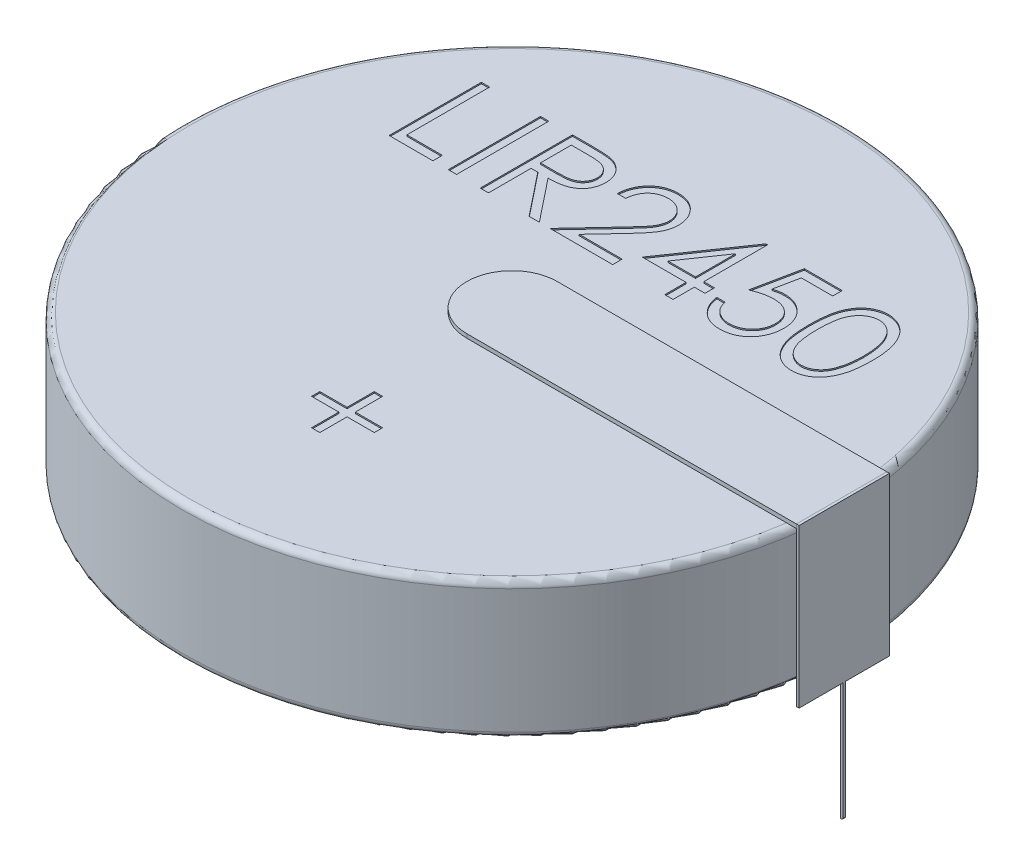
SolidWorks part; units mm, degrees
ref_plane "Plan de face" through (0, 0, 0) normal (0, 0, 1) x (1, 0, 0)
ref_plane "Plan de dessus" through (0, 0, 0) normal (0, 1, 0) x (1, 0, 0)
ref_plane "Plan de droite" through (0, 0, 0) normal (1, 0, 0) x (0, 0, -1)
sketch "Esquisse1" plane through (0, 0, 0) normal (0, 1, 0) x (1, 0, 0)
  circle A0 centre (0, 0) radius 12.5
extrude "Boss.-Extru.1" add sketch "Esquisse1" along normal blind 5.21
fillet "Congé1" radius 0.25 1 edges at (0, 5.21, 12.5)
fillet "Congé2" radius 0.25 1 edges at (0, 0, 12.5)
sketch "Esquisse3" plane through (0, 5.21, 0) normal (0, 1, 0) x (1, 0, 0)
  line L0 (0, 1.7143) -> (12.5, 1.7143)
  line L1 (12.5, 1.7143) -> (12.5, -1.7143)
  line L2 (12.5, -1.7143) -> (0, -1.7143)
  arc A0 (0, 1.7143) -> (0, -1.7143) centre (0, 0) ccw
extrude "Boss.-Extru.2" add sketch "Esquisse3" along normal blind 0.15
sketch "Esquisse4" plane through (0, 5.36, 0) normal (0, 1, 0) x (1, 0, 0)
  line L1 (12.5, 1.7143) -> (12.6033, 1.7143)
  line L2 (12.5, 1.7143) -> (12.5, -1.7143)
  line L3 (12.5, -1.7143) -> (12.6033, -1.7143)
  line L4 (12.6033, 1.7143) -> (12.6033, -1.7143)
extrude "Boss.-Extru.8" add sketch "Esquisse4" against normal blind 6 separate body contours L4 L3 L2 L1
sketch "Esquisse5" plane through (12.6033, 0, 0) normal (1, 0, 0) x (0, 0, -1)
  line L0 (1.7143, -0.64) -> (-1.7143, -0.64) construction
  line L1 (0, -0.64) -> (0, -5.14) construction
  line L2 (0, -5.14) -> (0.05, -5.14) construction
  line L3 (0, -5.14) -> (-0.05, -5.14) construction
  line L5 (0.05, -5.14) -> (-0.05, -5.14)
  line L6 (0.05, -5.14) -> (0.05, -0.64)
  line L7 (0.05, -0.64) -> (-0.05, -0.64)
  line L8 (-0.05, -5.14) -> (-0.05, -0.64)
extrude "Boss.-Extru.9" add sketch "Esquisse5" against normal blind 0.1
fillet "Congé3" radius 0.05 1 edges at (12.6033, -5.14, 0)
ref_plane "Plan2" through (0, -5.14, 0) normal (0, -1, 0) x (-1, 0, 0)
sketch "Esquisse6" plane through (0, 5.21, 0) normal (0, 1, 0) x (1, 0, 0)
  line L0 (0, 0) -> (-12.5, 0) construction
  circle A0 centre (0, 0) radius 12.5 construction
ref_plane "Plan3" through (-12.5, 0, 0) normal (-1, 0, 0) x (0, 0, 1)
ref_plane "Plan4" through (0, 0, 0) normal (0, -1, 0) x (-1, 0, 0)
sketch "Esquisse8" plane through (0, 0, 0) normal (0, -1, 0) x (1, 0, 0)
  line L0 (-12.5, 2.728) -> (-12.5, -2.728) construction
  line L1 (-12.5, -1.7014) -> (-7.494, -1.7014)
  line L2 (-12.5, -1.7014) -> (-12.5, 1.6945)
  line L3 (-12.5, 1.6945) -> (-7.494, 1.6945)
  line L4 (-7.494, -1.7014) -> (-7.494, 1.6945)
extrude "Boss.-Extru.11" add sketch "Esquisse8" along normal blind 0.1
sketch "Esquisse10" plane through (0, -0.1, 0) normal (0, -1, 0) x (1, 0, 0)
  line L0 (-12.5, 2.728) -> (-12.5, -2.728) construction
  line L1 (-12.5, -1.7014) -> (-12.4, -1.7014)
  line L2 (-12.5, -1.7014) -> (-12.5, 1.6945)
  line L3 (-12.5, 1.6945) -> (-12.4, 1.6945)
  line L4 (-12.4, -1.7014) -> (-12.4, 1.6945)
  line L5 (-12.5, -1.7014) -> (-7.494, -1.7014) construction
  line L6 (-7.494, 1.6945) -> (-12.5, 1.6945) construction
  dimension "D1" = 0.1
extrude "Boss.-Extru.12" add sketch "Esquisse10" along normal blind 0.54
sketch "Esquisse11" plane through (-12.5, 0, 0) normal (-1, 0, 0) x (0, 0, 1)
  line L0 (-7.1535, -5.14) -> (7.1535, -5.14) construction
  line L1 (-0.05, -0.64) -> (0.05, -0.64)
  line L2 (-0.05, -0.64) -> (-0.05, -5.14)
  line L3 (-0.05, -5.14) -> (0.05, -5.14)
  line L4 (0.05, -0.64) -> (0.05, -5.14)
  line L5 (0.05, -0.64) -> (0.05, -5.14) construction
extrude "Boss.-Extru.13" add sketch "Esquisse11" against normal blind 0.1
sketch "Esquisse12" plane through (0, 5.21, 0) normal (0, 1, 0) x (1, 0, 0)
  text T0 "LIR2450"
extrude "Enlèv. mat.-Extru.1" cut sketch "Esquisse12" against normal blind 0.05
sketch "Esquisse13" plane through (0, 5.21, 0) normal (0, 1, 0) x (1, 0, 0)
  text T0 "+"
extrude "Enlèv. mat.-Extru.2" cut sketch "Esquisse13" against normal blind 0.05
